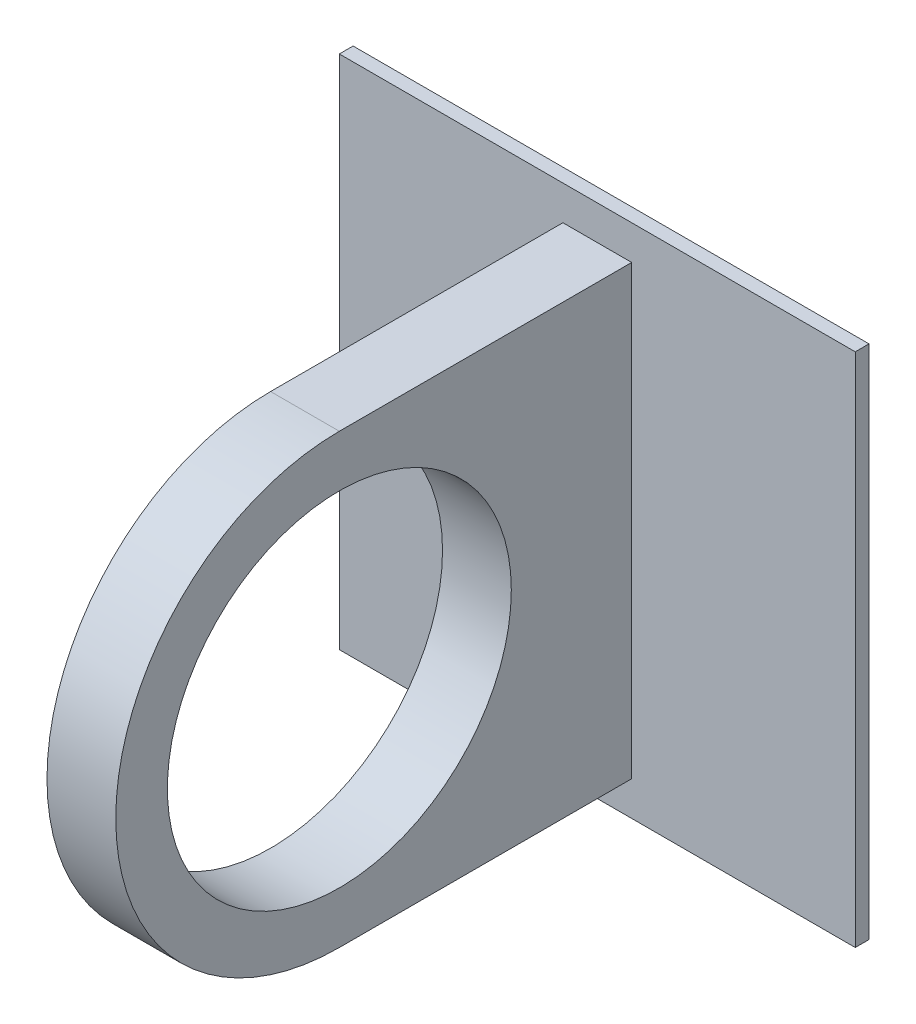
SolidWorks part; units mm, degrees
ref_plane "Front Plane" through (0, 0, 0) normal (0, 0, 1) x (1, 0, 0)
ref_plane "Top Plane" through (0, 0, 0) normal (0, 1, 0) x (1, 0, 0)
ref_plane "Right Plane" through (0, 0, 0) normal (1, 0, 0) x (0, 0, -1)
sketch "Sketch2" plane through (0, 0, 0) normal (0, 0, 1) x (1, 0, 0)
  line L1 (-9.525, -9.525) -> (9.525, -9.525)
  line L2 (-9.525, -9.525) -> (-9.525, 9.525)
  line L3 (-9.525, 9.525) -> (9.525, 9.525)
  line L4 (9.525, -9.525) -> (9.525, 9.525)
  line L5 (-9.525, -9.525) -> (9.525, 9.525) construction
  line L6 (-9.525, 9.525) -> (9.525, -9.525) construction
  point P0 (0, 0)
  dimension "D1" = 19.05
  dimension "D2" = 19.05
extrude "Boss-Extrude1" add sketch "Sketch2" along normal blind 0.508
sketch "Sketch3" plane through (0, 0, 0.508) normal (0, 0, 1) x (1, 0, 0)
  line L0 (0, 9.525) -> (0, -9.525) construction
  line L1 (9.525, 9.525) -> (-9.525, 9.525) construction
  line L2 (-9.525, -9.525) -> (9.525, -9.525) construction
  line L3 (-9.525, 0) -> (9.525, 0) construction
  line L4 (-9.525, 9.525) -> (-9.525, -9.525) construction
  line L5 (9.525, -9.525) -> (9.525, 9.525) construction
  line L7 (-1.27, -8.255) -> (1.27, -8.255)
  line L8 (-1.27, -8.255) -> (-1.27, 8.255)
  line L9 (-1.27, 8.255) -> (1.27, 8.255)
  line L10 (1.27, -8.255) -> (1.27, 8.255)
  line L11 (-1.27, -8.255) -> (1.27, 8.255) construction
  line L12 (-1.27, 8.255) -> (1.27, -8.255) construction
  point P12 (0, 0)
  dimension "D1" = 16.51
  dimension "D2" = 2.54
extrude "Boss-Extrude2" add sketch "Sketch3" along normal blind 19.05
sketch "Sketch4" plane through (1.27, 0, 0) normal (1, 0, 0) x (0, 0, -1)
  line L1 (-19.558, 0) -> (-0.508, 0) construction
  line L2 (-19.558, -8.255) -> (-19.558, 8.255) construction
  line L3 (-0.508, -9.525) -> (-0.508, 9.525) construction
  circle A0 centre (-11.303, 0) radius 8.255 construction
  circle A1 centre (-11.303, 0) radius 6.35
  point P20 (-11.303, 49.176)
  point P21 (-97.2471, 35.4175)
  point P22 (0, 0)
  dimension "D1" = 16.51
  dimension "D3" = 12.7
  dimension "D2" = 8.255
extrude "Cut-Extrude1" cut sketch "Sketch4" against normal up to next
sketch "Sketch9" plane through (1.27, 0, 0) normal (1, 0, 0) x (0, 0, -1)
  line L0 (-11.303, 0) -> (-11.303, 7.62) construction
  arc A0 (-11.303, 10.4775) -> (-11.303, -10.4775) centre (-11.303, 0) ccw construction
  arc A1 (-11.303, 12.7) -> (-11.303, -12.7) centre (-11.303, 0) ccw
  arc A2 (-11.303, 8.255) -> (-11.303, -8.255) centre (-11.303, 0) ccw
  arc A3 (-11.303, 8.255) -> (-11.303, 12.7) centre (-11.303, 10.4775) ccw
  arc A4 (-11.303, -12.7) -> (-11.303, -8.255) centre (-11.303, -10.4775) ccw
  point P4 (-21.7805, 0)
  point P10 (0, 0)
  point P11 (0, 0)
  dimension "D2" = 12.7
  dimension "D1" = 16.51
extrude "Cut-Extrude2" cut sketch "Sketch9" against normal up to next contours A2 A4 A1 A3
